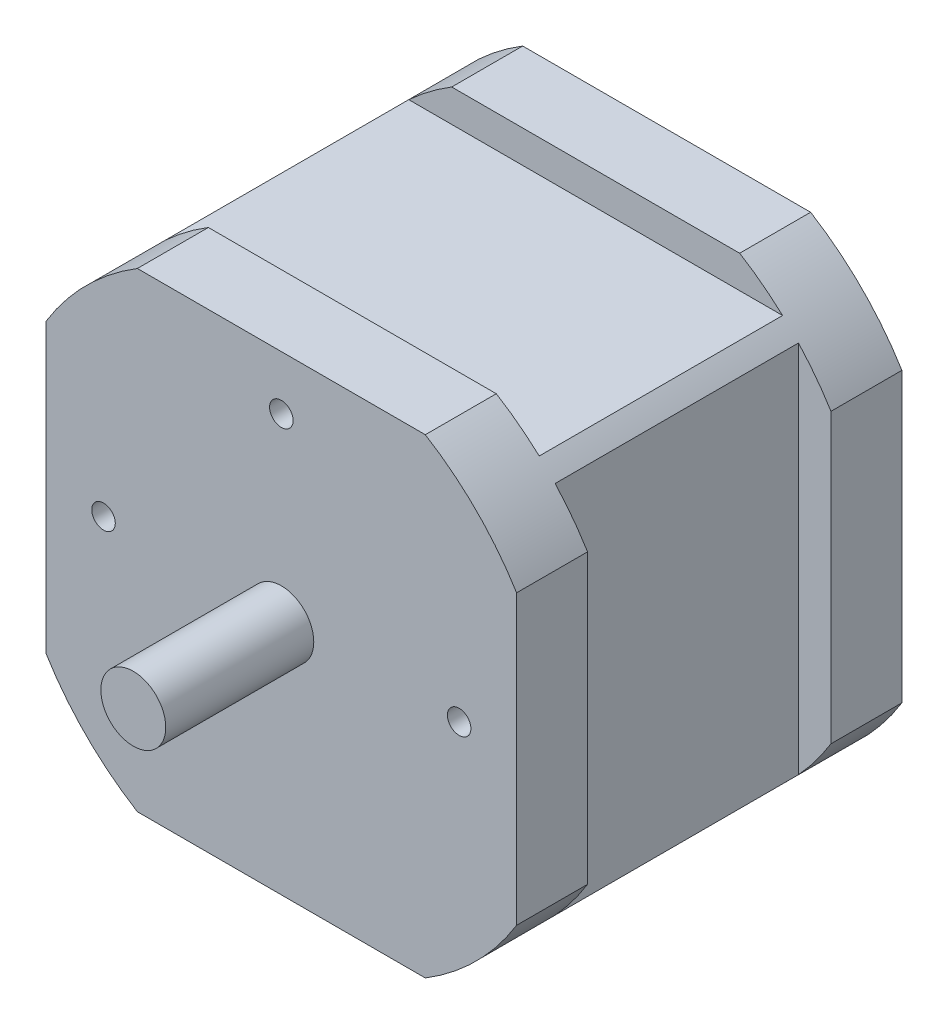
SolidWorks part; units mm, degrees
material "1.4511 (X3CrNb17)"
ref_plane "前视基准面" through (0, 0, 0) normal (0, 0, 1) x (1, 0, 0)
ref_plane "上视基准面" through (0, 0, 0) normal (0, 1, 0) x (1, 0, 0)
ref_plane "右视基准面" through (0, 0, 0) normal (1, 0, 0) x (0, 0, -1)
sketch "草图1" plane through (0, 0, 0) normal (0, 0, 1) x (1, 0, 0)
  line L1 (-25, 25) -> (25, 25)
  line L2 (-25, 25) -> (-25, -25)
  line L3 (-25, -25) -> (25, -25)
  line L4 (25, 25) -> (25, -25)
  line L5 (-25, 25) -> (25, -25) construction
  line L6 (-25, -25) -> (25, 25) construction
  point P0 (0, 0)
  dimension "D1" = 50
  dimension "D2" = 50
extrude "凸台-拉伸1" add sketch "草图1" along normal blind 30
sketch "草图2" plane through (0, 0, 30) normal (0, 0, 1) x (1, 0, 0)
  line L1 (-29, 29) -> (29, 29)
  line L2 (-29, 29) -> (-29, -29)
  line L3 (-29, -29) -> (29, -29)
  line L4 (29, 29) -> (29, -29)
  line L5 (-29, 29) -> (29, -29) construction
  line L6 (-29, -29) -> (29, 29) construction
  point P0 (0, 0)
  dimension "D1" = 58
  dimension "D2" = 58
extrude "凸台-拉伸2" add sketch "草图2" along normal blind 8.75
sketch "草图3" plane through (0, 0, 0) normal (0, 0, -1) x (-1, 0, 0)
  line L1 (-29, 29) -> (29, 29)
  line L2 (-29, 29) -> (-29, -29)
  line L3 (-29, -29) -> (29, -29)
  line L4 (29, 29) -> (29, -29)
  line L5 (-29, 29) -> (29, -29) construction
  line L6 (-29, -29) -> (29, 29) construction
  point P0 (0, 0)
extrude "凸台-拉伸3" add sketch "草图3" along normal blind 8.75
sketch "草图4" plane through (0, 0, 38.75) normal (0, 0, 1) x (1, 0, 0)
  circle A0 centre (0, 0) radius 34
  dimension "D1" = 68
sketch "草图6" plane through (0, 0, 38.75) normal (0, 0, 1) x (1, 0, 0)
  circle A0 centre (0, 0) radius 4
  dimension "D1" = 8
extrude "凸台-拉伸4" add sketch "草图6" along normal blind 18.25
extrude "切除-拉伸2" cut sketch "草图4" against normal through all flip side to cut contours A0
sketch "草图8" plane through (0, 0, 38.75) normal (0, 0, 1) x (1, 0, 0)
  line L0 (-21.92, 0.43) -> (21.92, 0.43) construction
  point P0 (0, 22.35)
  point P3 (0, 0.43)
  dimension "D1" = 0.43
  dimension "D2" = 43.84
  dimension "D3" = 22.35
hole_wizard "M3.5 螺纹孔1" positions "草图9" profile "草图10" tap size "M3.5" standard "GB"
sketch "草图9" plane through (0, 0, 38.75) normal (0, 0, 1) x (1, 0, 0)
  point P0 (0, 22.35)
  point P3 (-21.92, 0.43)
  point P6 (21.92, 0.43)
sketch "草图10" plane through (0, 22.35, 38.75) normal (1, 0, 0) x (0, -1, 0)
  line L0 (0, 0) -> (0, 8.8712)
  line L1 (0, 8.8712) -> (1.45, 8)
  line L2 (1.45, 8) -> (1.45, 0)
  line L5 (1.45, 0) -> (0, 0)
  line L10 (0, 8.8712) -> (-1.45, 8) construction
  line L11 (0, -6.35) -> (0, 107.95) construction
  dimension "螺纹孔钻头直径" = 2.9
  dimension "螺纹孔钻头深度" = 8
  dimension "导头角度" = 118
cosmetic thread "孔螺蚊线1" parameters "D1"=7, "D2"=3.5
cosmetic thread "孔螺蚊线2" parameters "D1"=7, "D2"=3.5
cosmetic thread "孔螺蚊线3" parameters "D1"=7, "D2"=3.5
